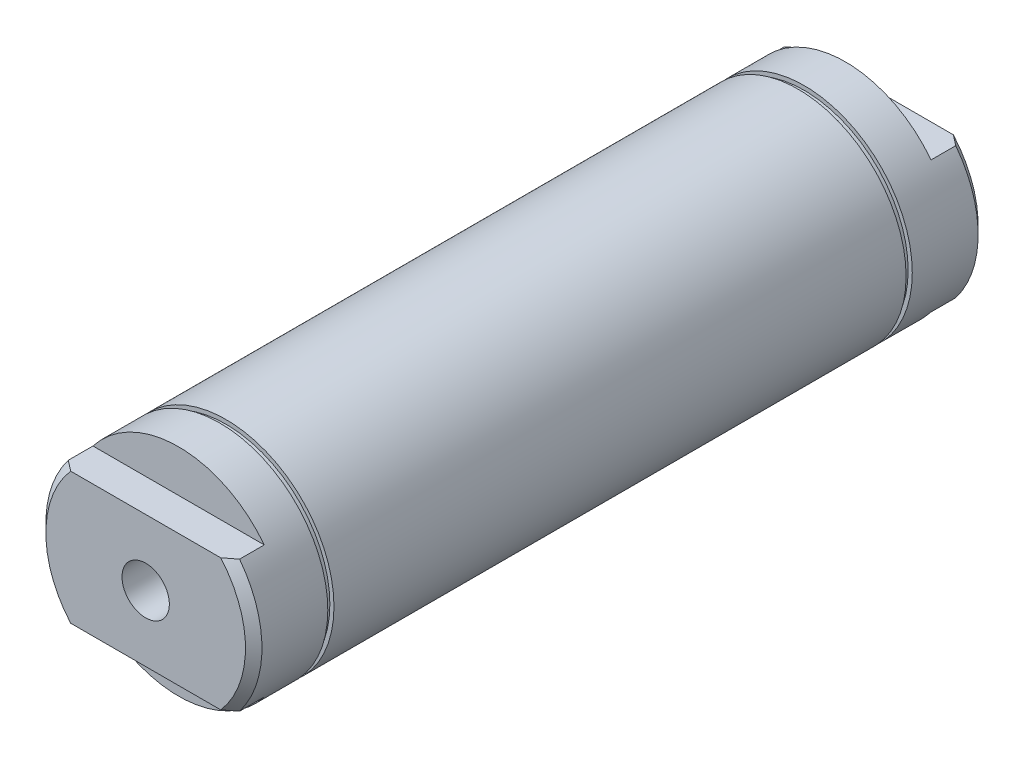
SolidWorks part; units mm, degrees
ref_plane "Front Plane" through (0, 0, 0) normal (0, 0, 1) x (1, 0, 0)
ref_plane "Top Plane" through (0, 0, 0) normal (0, 1, 0) x (1, 0, 0)
ref_plane "Right Plane" through (0, 0, 0) normal (1, 0, 0) x (0, 0, -1)
sketch "Sketch1" plane through (0, 0, 0) normal (0, 0, 1) x (1, 0, 0)
  circle A0 centre (0, 0) radius 26.25
  dimension "D1" = 52.5
extrude "Boss-Extrude1" add sketch "Sketch1" along normal mid plane 178
sketch "Sketch2" plane through (0, 0, 89) normal (0, 0, 1) x (1, 0, 0)
  line L0 (-20.8102, 16) -> (20.8102, 16)
  line L1 (20.8102, -16) -> (-20.8102, -16)
  circle A0 centre (0, 0) radius 26.25 construction
  arc A1 (-20.8102, -16) -> (20.8102, -16) centre (0, 0) ccw
  arc A2 (20.8102, 16) -> (-20.8102, 16) centre (0, 0) ccw
  dimension "D1" = 32
extrude "Cut-Extrude1" cut sketch "Sketch2" against normal blind 8
sketch "Sketch3" plane through (0, 0, 89) normal (0, 0, 1) x (1, 0, 0)
  circle A0 centre (0, 0) radius 6.35
  dimension "D1" = 12.7
sketch "Sketch28" plane through (0, 0, 89) normal (0, 0, 1) x (1, 0, 0)
  point P0 (0, 0)
hole_wizard "1/2-20 Tapped Hole3" positions "Sketch28" profile "Sketch27" tap size "1/2-20" standard "ANSI Inch"
sketch "Sketch27" plane through (0, 0, 89) normal (1, 0, 0) x (0, -1, 0)
  line L0 (0, 0) -> (0, 13.4576)
  line L1 (0, 13.4576) -> (5.7544, 10)
  line L2 (5.7544, 10) -> (5.7544, 0)
  line L5 (5.7544, 0) -> (0, 0)
  line L10 (0, 13.4576) -> (-5.7544, 10) construction
  line L11 (0, -6.35) -> (0, 107.95) construction
  dimension "Tap Drill Dia." = 11.5087
  dimension "Tap Drill Depth" = 10
  dimension "Drill Angle" = 118
cosmetic thread "Hole Thread1" parameters "D1"=25.4, "D2"=12.7
mirror "Mirror2" about plane through (0, 0, 0) normal (0, 0, 1) of "Cut-Extrude1", "1/2-20 Tapped Hole3"
cosmetic thread "Hole Thread2" parameters "D1"=25.4, "D2"=12.7
sketch "Sketch29" plane through (0, 0, 0) normal (0, 1, 0) x (1, 0, 0)
  line L0 (26.25, -89) -> (26.25, 89) construction
  line L1 (26.25, 71) -> (25.25, 71)
  line L2 (26.25, 71) -> (26.25, 69.5)
  line L3 (26.25, 69.5) -> (25.25, 69.5)
  line L4 (25.25, 71) -> (25.25, 69.5)
  line L5 (26.25, 89) -> (20.8102, 89) construction
  dimension "D1" = 18
  dimension "D2" = 1
  dimension "D3" = 1.5
ref_axis "Axis1" through (0, 0, 89) along (0, 0, -1)
revolve "Cut-Revolve1" cut sketch "Sketch29" angle 360 about axis through (0, 0, 89) along (0, 0, -1)
mirror "Mirror3" about plane through (0, 0, 0) normal (0, 0, 1) of "Cut-Revolve1"
chamfer "Chamfer1" distance 2 angle 45 4 edges at (-26.25, 0, 89) (26.25, 0, 89) (26.25, 0, -89) (-26.25, 0, -89)
